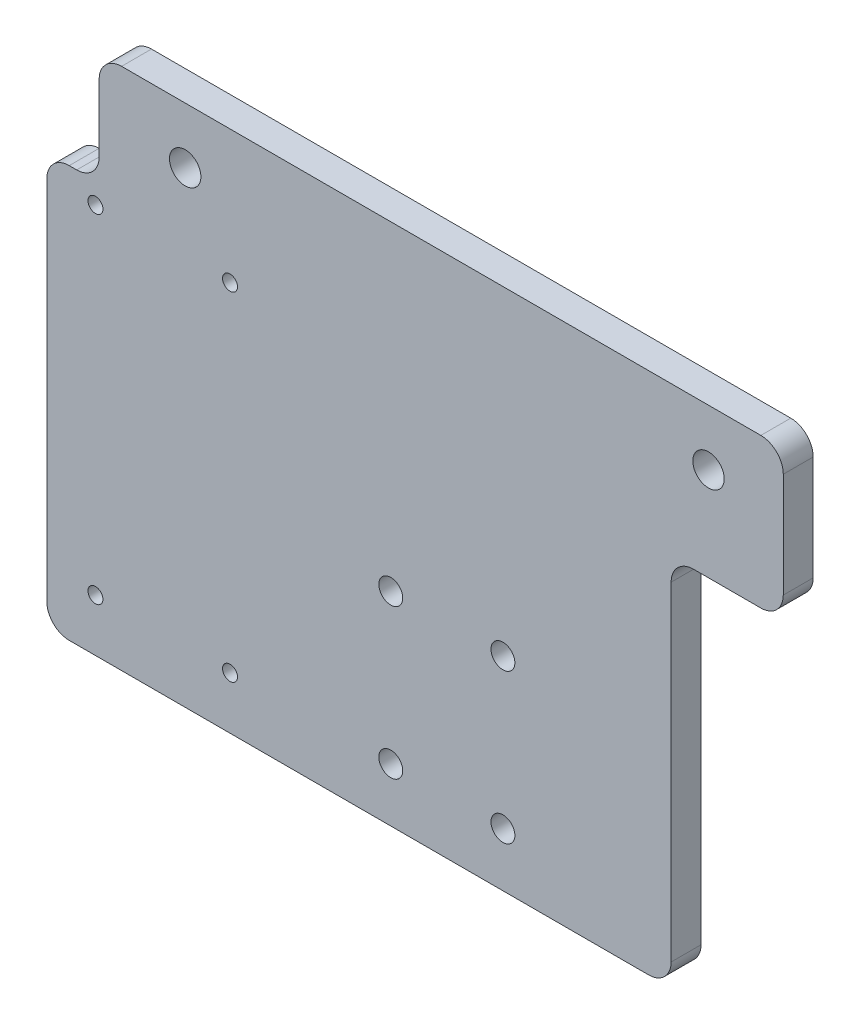
SolidWorks part; units mm, degrees
material "默认 (3)"
ref_plane "前视基准面" through (0, 0, 0) normal (0, 0, 1) x (1, 0, 0)
ref_plane "上视基准面" through (0, 0, 0) normal (0, 1, 0) x (1, 0, 0)
ref_plane "右视基准面" through (0, 0, 0) normal (1, 0, 0) x (0, 0, -1)
other "Configuration Table"
sketch "草图1" plane through (0, 0, 0) normal (0, 0, 1) x (1, 0, 0)
  line L0 (0, 0) -> (0, -50000) construction
  line L1 (-125, 15) -> (125, 15)
  line L2 (-125, 15) -> (-125, -15)
  line L3 (-125, -15) -> (125, -15)
  line L4 (125, 15) -> (125, -15)
  line L5 (-125, 15) -> (125, -15) construction
  line L6 (-125, -15) -> (125, 15) construction
  line L7 (-115, -10) -> (-115, 10) construction
  circle A0 centre (-115, -10) radius 1.5
  circle A1 centre (-115, 10) radius 1.5
  circle A2 centre (115, 10) radius 1.5
  circle A3 centre (115, -10) radius 1.5
  point P0 (0, 0)
  dimension "D6" = 5
  dimension "D7" = 3
  dimension "D1" = 250
  dimension "D2" = 30
  dimension "D4" = 20
  dimension "D5" = 10
  dimension "D3" = 2
extrude "凸台-拉伸1" add sketch "草图1" along normal blind 4
sketch "草图2" plane through (0, 0, 4) normal (0, 0, 1) x (1, 0, 0)
  line L0 (0, 0) -> (0, -50000) construction
  line L1 (0, 9) -> (50000, 9) construction
  line L2 (-23, 2.5) -> (23, 2.5) construction
  line L3 (-23, 2.5) -> (-23, 15.5) construction
  line L4 (-125, -15) -> (125, -15) construction
  circle A0 centre (-23, 2.5) radius 3
  circle A1 centre (23, 2.5) radius 3
  circle A2 centre (23, 15.5) radius 3
  circle A3 centre (-23, 15.5) radius 3
  dimension "D5" = 6
  dimension "D3" = 46
  dimension "D4" = 13
  dimension "D6" = 24
  dimension "D1" = 2
  dimension "D2" = 2
extrude "切除-拉伸1" cut sketch "草图2" against normal through all
sketch "草图3" plane through (0, 0, 4) normal (0, 0, 1) x (1, 0, 0)
  line L0 (0, 54.5) -> (0, -49945.5) construction
  line L1 (-125, 85) -> (125, 85)
  line L2 (-125, 85) -> (-125, 15)
  line L3 (-125, 15) -> (125, 15)
  line L4 (125, 85) -> (125, 15)
  line L5 (-125, 85) -> (125, 15) construction
  line L6 (-125, 15) -> (125, 85) construction
  line L8 (-115, 10) -> (-115, 30) construction
  circle A4 centre (-115, 10) radius 1.5 construction
  circle A5 centre (-115, 10) radius 1.5
  circle A6 centre (-115, 30) radius 1.5
  circle A7 centre (-115, 50) radius 1.5
  circle A8 centre (-115, 70) radius 1.5
  circle A9 centre (-115, 90) radius 1.5
  circle A10 centre (115, 10) radius 1.5
  circle A11 centre (115, 30) radius 1.5
  circle A12 centre (115, 50) radius 1.5
  circle A13 centre (115, 70) radius 1.5
  circle A14 centre (-35, 77.5) radius 2.1
  circle A15 centre (35, 77.5) radius 2.1
  point P0 (0, 50)
  dimension "D4" = 70
  dimension "D2" = 4.2
  dimension "D3" = 7.5
  dimension "D1" = 70
  dimension "D7" = 20
  dimension "D6" = 5
extrude "凸台-拉伸2" add sketch "草图3" against normal blind 4
sketch "草图4" plane through (0, 0, 4) normal (0, 0, 1) x (1, 0, 0)
  line L1 (-125, 85) -> (125, 85) construction
  line L8 (-125, -15) -> (125, -15) construction
  line L9 (-97, 70) -> (-48, 70)
  line L10 (-100, 67) -> (-100, 3)
  line L11 (-97, 0) -> (-48, 0)
  line L12 (-45, 67) -> (-45, 3)
  line L13 (-100, 70) -> (-45, 0) construction
  line L14 (-100, 0) -> (-45, 70) construction
  line L15 (-125, 85) -> (-125, -15) construction
  line L16 (97, 0) -> (48, 0)
  line L17 (45, 67) -> (45, 3)
  line L18 (97, 70) -> (48, 70)
  line L19 (100, 67) -> (100, 3)
  arc A4 (-48, 0) -> (-45, 3) centre (-48, 3) ccw
  arc A5 (-100, 3) -> (-97, 0) centre (-97, 3) ccw
  arc A6 (-48, 70) -> (-45, 67) centre (-48, 67) cw
  arc A7 (-97, 70) -> (-100, 67) centre (-97, 67) ccw
  arc A8 (48, 0) -> (45, 3) centre (48, 3) cw
  arc A9 (48, 70) -> (45, 67) centre (48, 67) ccw
  arc A10 (100, 3) -> (97, 0) centre (97, 3) cw
  arc A11 (97, 70) -> (100, 67) centre (97, 67) cw
  point P10 (-72.5, 35)
  dimension "D4" = 15
  dimension "D5" = 15
  dimension "D6" = 25
  dimension "D7" = 55
extrude "切除-拉伸2" cut sketch "草图4" against normal through all
fillet "圆角1" radius 5 4 edges at (125, -15, 2) (125, 85, 2) (-125, -15, 2) (-125, 85, 2)
sketch "草图5" plane through (0, 0, 4) normal (0, 0, 1) x (1, 0, 0)
  circle A0 centre (-23, 15.5) radius 3
  circle A1 centre (23, 15.5) radius 3
  dimension "D1" = 6
extrude "切除-拉伸3" cut sketch "草图5" against normal through all
sketch "草图8" plane through (0, 0, 4) normal (0, 0, 1) x (1, 0, 0)
  line L0 (-48, 70) -> (-97, 70) construction
  line L1 (-45, 70) -> (-65, 70)
  line L2 (-45, 70) -> (-45, 20)
  line L3 (-45, 20) -> (-65, 20)
  line L4 (-65, 70) -> (-65, 20)
  line L5 (-45, 3) -> (-45, 67) construction
  dimension "D1" = 50
  dimension "D2" = 20
extrude "凸台-拉伸4" add sketch "草图8" against normal up to surface (4 mm away) up to face at (-72.5, 35, 0)
sketch "草图9" plane through (0, 0, 4) normal (0, 0, 1) x (1, 0, 0)
  line L0 (-65, 20) -> (-45, 20) construction
  line L1 (-65, 70) -> (-65, 20) construction
  circle A0 centre (-47, 22) radius 1
  circle A1 centre (-29, 22) radius 1
  circle A2 centre (-47, 67.2) radius 1
  circle A3 centre (-29, 67.2) radius 1
  dimension "D1" = 2
  dimension "D4" = 2
  dimension "D5" = 18
  dimension "D2" = 2
  dimension "D3" = 2
extrude "切除-拉伸4" cut sketch "草图9" against normal blind 10
fillet "圆角3" [suppressed] radius 3
sketch "草图10" plane through (0, 0, 4) normal (0, 0, 1) x (1, 0, 0)
  line L0 (0, 0) -> (0, 130.9934) construction
  line L1 (35, 15) -> (35, -15)
  line L2 (35, 15) -> (-35, 15)
  line L3 (0, 15) -> (0, -15)
  line L4 (35, -15) -> (-35, -15)
  line L5 (-35, 15) -> (-35, -15)
  line L6 (-120, -15) -> (120, -15) construction
  dimension "D1" = 70
  dimension "D2" = 30
  dimension "D3" = 30
extrude "切除-拉伸5" cut sketch "草图10" against normal blind 10 contours L2 L5 L4 L3 | L4 L1 L2 L3
sketch "草图11" plane through (0, 0, 4) normal (0, 0, 1) x (1, 0, 0)
  line L1 (-35, 15) -> (35, 15)
  line L2 (-35, 15) -> (-35, 19.6041)
  line L3 (-35, 19.6041) -> (35, 19.6041)
  line L4 (35, 15) -> (35, 19.6041)
extrude "凸台-拉伸5" add sketch "草图11" against normal up to surface (4 mm away) up to face at (-28, 22, 0)
fillet "圆角4" radius 10 4 edges at (35, 15, 2) (35, -15, 2) (-35, -15, 2) (-35, 15, 2)
sketch "草图12" plane through (0, 0, 4) normal (0, 0, 1) x (1, 0, 0)
  line L0 (0, 85) -> (0, -53.6278) construction
  line L1 (-120, 85) -> (120, 85) construction
  line L2 (-159.4821, 67) -> (-159.4821, 15)
  line L3 (45, 67) -> (144.5907, 67)
  line L4 (45, 67) -> (45, 102.3315)
  line L5 (45, 102.3315) -> (144.5907, 102.3315)
  line L6 (144.5907, 67) -> (144.5907, 102.3315)
  line L7 (45, 67) -> (137.7054, 67)
  line L8 (45, 67) -> (45, 15)
  line L11 (25, 15) -> (159.4821, 15)
  line L12 (25, 15) -> (25, -21.4432)
  line L13 (25, -21.4432) -> (159.4821, -21.4432)
  line L14 (159.4821, 15) -> (159.4821, -21.4432)
  line L15 (45, 67) -> (159.4821, 67)
  line L16 (45, 67) -> (45, 15)
  line L17 (45, 15) -> (159.4821, 15)
  line L18 (159.4821, 67) -> (159.4821, 15)
  line L19 (-45, 15) -> (-159.4821, 15)
  line L20 (-56.5072, 67) -> (-56.5072, 15)
  line L21 (-56.5072, 67) -> (-159.4821, 67)
  line L22 (-159.4821, 15) -> (-159.4821, -21.4432)
  line L23 (-25, -21.4432) -> (-159.4821, -21.4432)
  line L24 (-25, 15) -> (-25, -21.4432)
  line L25 (-25, 15) -> (-159.4821, 15)
  line L26 (-56.5072, 67) -> (-56.5072, 102.3315)
  line L27 (-56.5072, 67) -> (-137.7054, 67)
  line L28 (-144.5907, 67) -> (-144.5907, 102.3315)
  line L29 (-56.5072, 102.3315) -> (-144.5907, 102.3315)
  line L31 (-56.5072, 67) -> (-144.5907, 67)
extrude "切除-拉伸6" cut sketch "草图12" against normal blind 10
fillet "圆角5" [suppressed] radius 2
sketch "草图14" plane through (0, 0, 4) normal (0, 0, 1) x (1, 0, 0)
  line L0 (45, 15) -> (-45, 15) construction
  line L1 (-45, 20) -> (-56.5072, 20)
  line L2 (-45, 20) -> (-45, 15)
  line L3 (-45, 15) -> (-56.5072, 15)
  line L4 (-56.5072, 20) -> (-56.5072, 15)
  line L5 (-56.5072, 85) -> (-56.5072, 20) construction
extrude "凸台-拉伸6" add sketch "草图14" against normal up to surface (4 mm away) up to face at (-28, 22, 0)
sketch "草图15" plane through (0, 0, 4) normal (0, 0, 1) x (1, 0, 0)
  line L0 (-56.5072, 85) -> (45, 85) construction
  line L1 (45, 15) -> (30, 15)
  line L2 (45, 15) -> (45, 65)
  line L3 (45, 65) -> (30, 65)
  line L4 (30, 15) -> (30, 65)
  line L5 (-56.5072, 15) -> (-53.5072, 15)
  line L6 (-56.5072, 15) -> (-56.5072, 70)
  line L7 (-56.5072, 70) -> (-53.5072, 70)
  line L8 (-53.5072, 15) -> (-53.5072, 70)
  line L9 (-56.5072, 70) -> (-46.5072, 70)
  line L10 (-56.5072, 70) -> (-56.5072, 85)
  line L11 (-56.5072, 85) -> (-46.5072, 85)
  line L12 (-46.5072, 70) -> (-46.5072, 85)
  line M11 (45, 85) -> (-56.5072, 85)
  line M12 (-56.5072, 85) -> (-56.5072, 15)
  line M13 (-56.5072, 15) -> (45, 15)
  line M14 (45, 15) -> (45, 85)
  dimension "D1" = 50
  dimension "D2" = 15
  dimension "D3" = 55
  dimension "D4" = 3
  dimension "D5" = 10
extrude "切除-拉伸7" cut sketch "草图15" against normal blind 10 contours L9 L12 L7 M11 M12 | L8 L7 M13 M12 | L4 L3 M13 M14
fillet "圆角6" radius 3 8 edges at (-53.5072, 70, 2) (-46.5072, 70, 2) (-46.5072, 85, 2) (45, 85, 2) (45, 65, 2) (30, 65, 2) (-53.5072, 15, 2) (30, 15, 2)
sketch "草图16" plane through (0, 0, 4) normal (0, 0, 1) x (1, 0, 0)
  line L0 (-35, 77.5) -> (35, 77.5)
  line L1 (0, 77.5) -> (0, -5.4389) construction
  line L2 (-43.5072, 85) -> (42, 85) construction
  line L3 (0, 57.5) -> (0, -25.4389) construction
  circle A0 centre (-7.5, 42.2) radius 1.6
  circle A1 centre (7.5, 42.2) radius 1.6
  circle A2 centre (-7.5, 22.2) radius 1.6
  circle A3 centre (7.5, 22.2) radius 1.6
  dimension "D1" = 3.2
  dimension "D2" = 15
  dimension "D3" = 42.8
  dimension "D5" = 20
  dimension "D4" = 2
extrude "切除-拉伸8" cut sketch "草图16" against normal blind 10 contours A0 | A1 | A2 | A3
chamfer "倒角2" distance 1 angle 45 1 edges at (-5.9, 42.2, 0)
